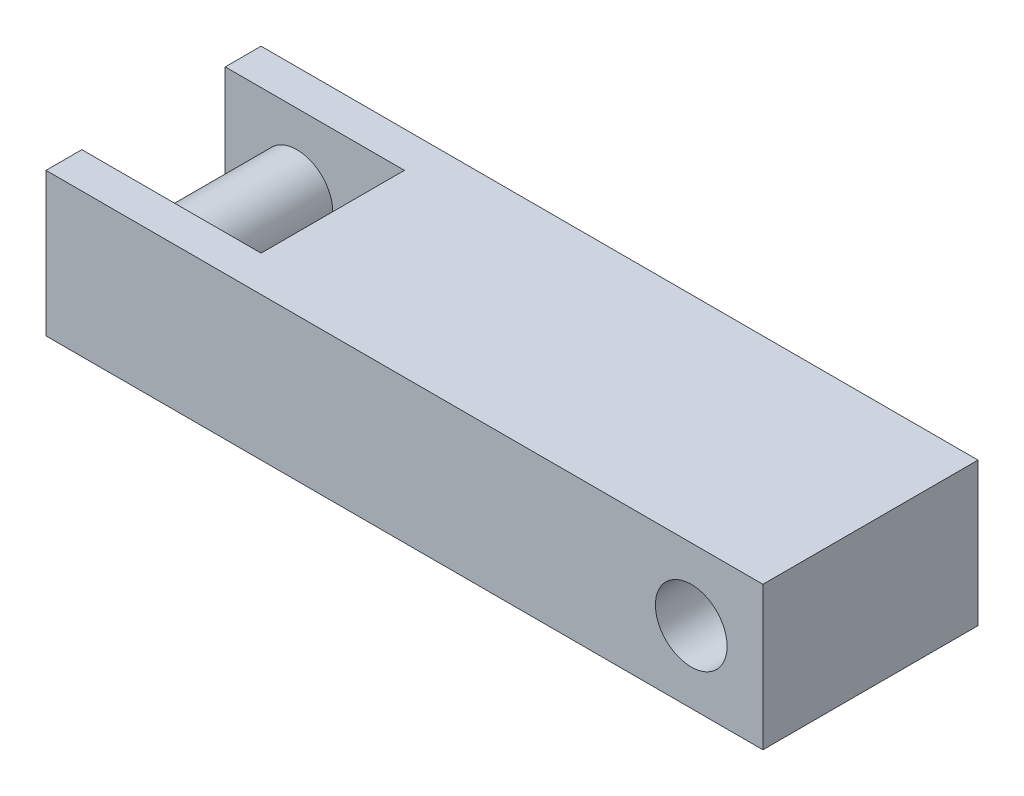
SolidWorks part; units mm, degrees
ref_plane "Front Plane" through (0, 0, 0) normal (0, 0, 1) x (1, 0, 0)
ref_plane "Top Plane" through (0, 0, 0) normal (0, 1, 0) x (1, 0, 0)
ref_plane "Right Plane" through (0, 0, 0) normal (1, 0, 0) x (0, 0, -1)
sketch "Sketch1" plane through (0, 0, 0) normal (0, 0, 1) x (1, 0, 0)
  line L0 (0, 10) -> (100, 10) construction
  line L1 (0, 0) -> (100, 0)
  line L2 (0, 0) -> (0, 20)
  line L3 (0, 20) -> (100, 20)
  line L4 (100, 0) -> (100, 20)
  circle A1 centre (90, 10) radius 5
  dimension "D3" = 10
  dimension "D1" = 100
  dimension "D2" = 20
  dimension "D5" = 10
extrude "Boss-Extrude1" add sketch "Sketch1" along normal blind 30
sketch "Sketch2" plane through (0, 20, 0) normal (0, 1, 0) x (1, 0, 0)
  line L0 (100, -15) -> (0, -15) construction
  line L1 (100, -30) -> (100, 0) construction
  line L2 (0, -55) -> (0, 55) construction
sketch "Sketch4" plane through (0, 0, 0) normal (-1, 0, 0) x (0, 0, 1)
  line L0 (30, 20) -> (0, 20) construction
  line L1 (5, 20) -> (25, 20)
  line L2 (5, 20) -> (5, 0)
  line L3 (5, 0) -> (25, 0)
  line L4 (25, 20) -> (25, 0)
  line L5 (30, 0) -> (0, 0) construction
  line L6 (0, 20) -> (0, 0) construction
  dimension "D1" = 20
  dimension "D2" = 5
extrude "Cut-Extrude1" cut sketch "Sketch4" against normal blind 25
sketch "Sketch5" plane through (0, 0, 30) normal (0, 0, 1) x (1, 0, 0)
  line L0 (100, 10) -> (0, 10) construction
  line L1 (100, 0) -> (100, 20) construction
  line L2 (0, -11) -> (0, 11) construction
  circle A0 centre (10, 10) radius 5
  dimension "D1" = 10
extrude "Boss-Extrude2" add sketch "Sketch5" against normal through all
